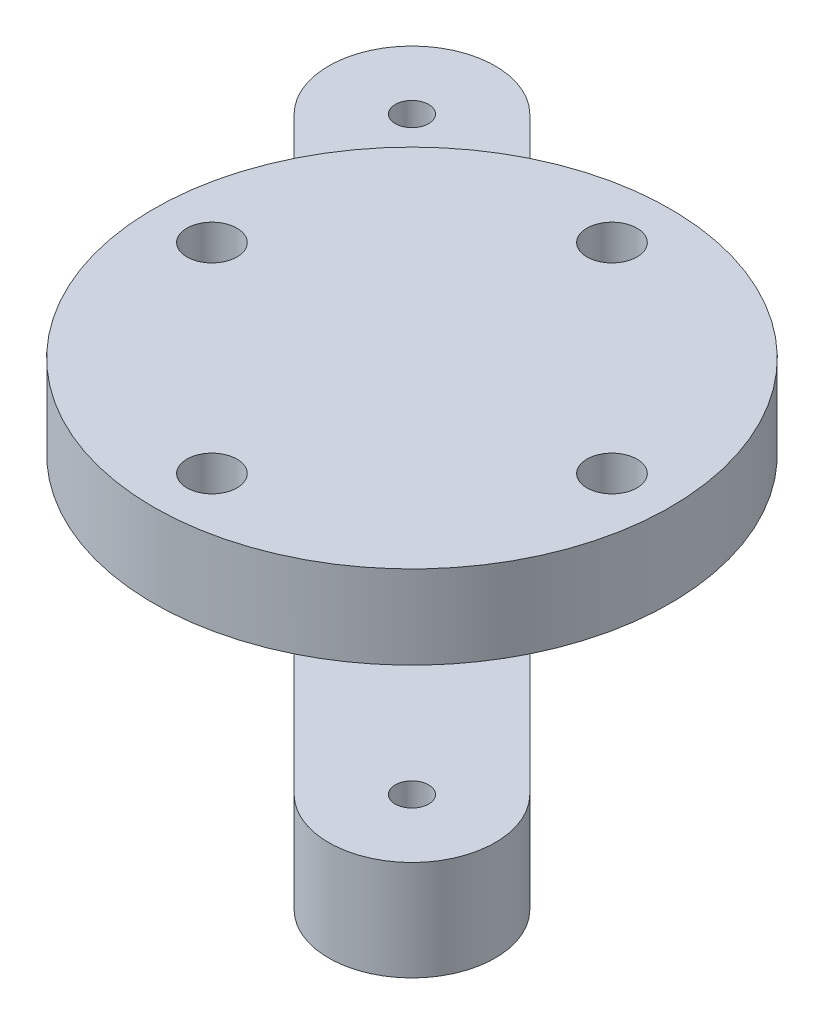
SolidWorks part; units mm, degrees
ref_plane "Front Plane" through (0, 0, 0) normal (0, 0, 1) x (1, 0, 0)
ref_plane "Top Plane" through (0, 0, 0) normal (0, 1, 0) x (1, 0, 0)
ref_plane "Right Plane" through (0, 0, 0) normal (1, 0, 0) x (0, 0, -1)
sketch "Sketch1" plane through (0, 0, 0) normal (0, 1, 0) x (1, 0, 0)
  circle A0 centre (0, 0) radius 31
  dimension "D1" = 62
extrude "Boss-Extrude1" add sketch "Sketch1" along normal blind 10 contours A0
sketch "Sketch2" plane through (0, 10, 0) normal (0, 1, 0) x (1, 0, 0)
  line L0 (0, 31) -> (0, -31) construction
  line L1 (-31, 0) -> (31, 0) construction
  circle A0 centre (0, 0) radius 31 construction
  circle A1 centre (0, 24) radius 3
  circle A2 centre (24, 0) radius 3
  circle A3 centre (0, -24) radius 3
  circle A4 centre (-24, 0) radius 3
  circle A5 centre (0, 24) radius 5
  circle A6 centre (24, 0) radius 5
  circle A7 centre (0, -24) radius 5
  circle A8 centre (-24, 0) radius 5
  dimension "D1" = 6
  dimension "D2" = 6
  dimension "D6" = 6
  dimension "D8" = 6
  dimension "D10" = 10
  dimension "D11" = 10
  dimension "D12" = 10
  dimension "D13" = 10
  dimension "D3" = 24
  dimension "D4" = 7
  dimension "D5" = 24
  dimension "D7" = 24
  dimension "D9" = 24
extrude "Cut-Extrude11" cut sketch "Sketch2" against normal blind 10 contours A2 | A3 | A4 | A1
sketch "Sketch5" plane through (0, 0, 0) normal (0, 1, 0) x (1, 0, 0)
  circle A0 centre (0, 24) radius 5
  circle A1 centre (24, 0) radius 5
  circle A2 centre (0, -24) radius 5
  circle A3 centre (-24, 0) radius 5
  dimension "D1" = 10
  dimension "D2" = 10
  dimension "D3" = 10
  dimension "D4" = 10
extrude "Cut-Extrude14" cut sketch "Sketch5" along normal blind 5 contours A3 | A2 | A1 | A0
sketch "Sketch6" plane through (0, 0, 0) normal (0, 1, 0) x (1, 0, 0)
  line L0 (35.3553, -35.3553) -> (-35.3553, 35.3553) construction
  line L1 (28.2843, -42.4264) -> (-42.4264, 28.2843)
  line L2 (42.4264, -28.2843) -> (-28.2843, 42.4264)
  arc A0 (28.2843, -42.4264) -> (42.4264, -28.2843) centre (35.3553, -35.3553) ccw
  arc A1 (-28.2843, 42.4264) -> (-42.4264, 28.2843) centre (-35.3553, 35.3553) ccw
  circle A2 centre (-35.3553, 35.3553) radius 2
  circle A3 centre (35.3553, -35.3553) radius 2
  point P2 (0, 0)
  dimension "D1" = 20
  dimension "D4" = 4
  dimension "D5" = 4
  dimension "D2" = 50
  dimension "D3" = 70.7107
extrude "Boss-Extrude5" add sketch "Sketch6" against normal blind 12
